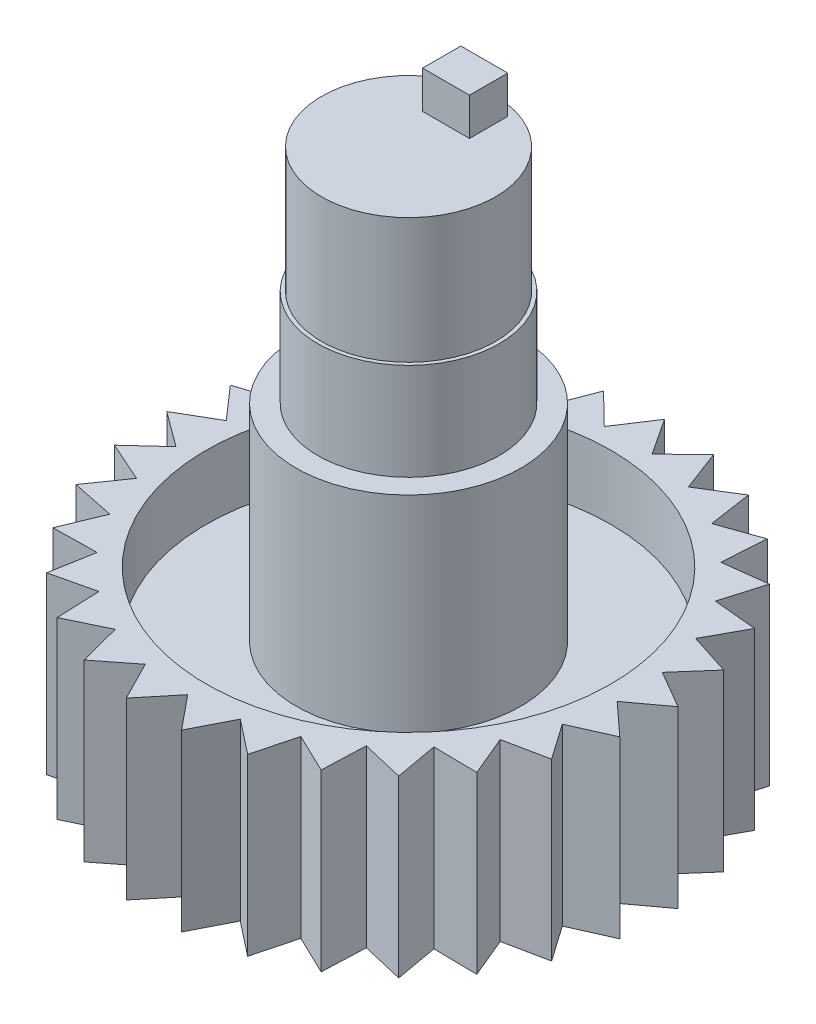
SolidWorks part; units mm, degrees
ref_plane "Front Plane" through (0, 0, 0) normal (0, 0, 1) x (1, 0, 0)
ref_plane "Top Plane" through (0, 0, 0) normal (0, 1, 0) x (1, 0, 0)
ref_plane "Right Plane" through (0, 0, 0) normal (1, 0, 0) x (0, 0, -1)
sketch "Sketch1" plane through (0, 0, 0) normal (0, 0, 1) x (1, 0, 0)
  line L8 (0, 0) -> (0, 24.17)
  line L9 (0, -55) -> (0, 55) construction
  line L10 (0, 24.17) -> (3.25, 24.17)
  line L11 (3.25, 24.17) -> (3.25, 19.49)
  line L12 (3.25, 19.49) -> (3.39, 19.49)
  line L13 (3.39, 19.49) -> (3.39, 15.87)
  line L14 (3.39, 15.87) -> (4.2, 15.87)
  line L15 (4.2, 15.87) -> (4.2, 8.17)
  line L16 (4.2, 8.17) -> (7.56, 8.17)
  line L17 (7.56, 8.17) -> (7.56, 10.57)
  line L18 (7.56, 10.57) -> (9.56, 10.57)
  line L19 (9.56, 10.57) -> (9.56, 4.04)
  line L20 (9.56, 4.04) -> (7.56, 4.04)
  line L21 (7.56, 4.04) -> (7.56, 6.89)
  line L22 (7.56, 6.89) -> (3.365, 6.89)
  line L23 (3.365, 6.89) -> (3.365, 2.46)
  line L24 (3.365, 2.46) -> (2, 2.46)
  line L25 (2, 2.46) -> (2, 0)
  line L26 (55, 0) -> (-55, 0) construction
  line L27 (2, 0) -> (0, 0)
  dimension "D1" = 6.53
  dimension "D2" = 4.2
  dimension "D3" = 9.56
  dimension "D4" = 3.39
  dimension "D5" = 3.25
  dimension "D6" = 4.68
  dimension "D7" = 8.3
  dimension "D8" = 16
  dimension "D9" = 13.6
  dimension "D10" = 2.85
  dimension "D11" = 3.365
  dimension "D12" = 2
  dimension "D13" = 2.46
  dimension "D14" = 4.43
  dimension "D15" = 2
  dimension "D16" = 2
revolve "Revolve1" add sketch "Sketch1" angle 360 about L8
sketch "Sketch2" plane through (0, 24.17, 0) normal (0, 1, 0) x (1, 0, 0)
  line L0 (0, -10.516) -> (0, 10.516) construction
  line L1 (-0.875, 2.83) -> (0.875, 2.83)
  line L2 (-0.875, 2.83) -> (-0.875, 1.4)
  line L3 (-0.875, 1.4) -> (0.875, 1.4)
  line L4 (0.875, 2.83) -> (0.875, 1.4)
  line L5 (-10.516, 0) -> (10.516, 0) construction
  point P4 (0, 2.83)
  dimension "D1" = 1.75
  dimension "D2" = 1.43
  dimension "D3" = 1.4
extrude "Boss-Extrude1" add sketch "Sketch2" along normal blind 1.4
sketch "Sketch3" plane through (0, 10.57, 0) normal (0, 1, 0) x (1, 0, 0)
  line L0 (0, 9.56) -> (-0.892, 8.2016)
  line L1 (0, -10.516) -> (0, 10.516) construction
  line L2 (-0.892, 8.2016) -> (0, 0) construction
  line L3 (0, 0) -> (0.892, 8.2016) construction
  line L4 (0.892, 8.2016) -> (0, 9.56)
  line L5 (2.6342, 7.8181) -> (2.0551, 9.3365)
  line L6 (2.0551, 9.3365) -> (0.892, 8.2016)
  line L7 (4.2533, 7.0691) -> (4.0141, 8.6764)
  line L8 (4.0141, 8.6764) -> (2.6342, 7.8181)
  line L9 (5.6735, 5.9895) -> (5.7855, 7.6106)
  line L10 (5.7855, 7.6106) -> (4.2533, 7.0691)
  line L11 (6.8284, 4.6298) -> (7.2863, 6.189)
  line L12 (7.2863, 6.189) -> (5.6735, 5.9895)
  line L13 (7.6641, 3.0536) -> (8.4464, 4.478)
  line L14 (8.4464, 4.478) -> (6.8284, 4.6298)
  line L15 (8.1413, 1.3347) -> (9.2115, 2.5576)
  line L16 (9.2115, 2.5576) -> (7.6641, 3.0536)
  line L17 (8.2379, -0.4466) -> (9.546, 0.5176)
  line L18 (9.546, 0.5176) -> (8.1413, 1.3347)
  line L19 (7.9493, -2.2071) -> (9.4341, -1.5466)
  line L20 (9.4341, -1.5466) -> (8.2379, -0.4466)
  line L21 (7.289, -3.8644) -> (8.881, -3.5385)
  line L22 (8.881, -3.5385) -> (7.9493, -2.2071)
  line L23 (6.2878, -5.3409) -> (7.9127, -5.3649)
  line L24 (7.9127, -5.3649) -> (7.289, -3.8644)
  line L25 (4.9927, -6.5678) -> (6.5744, -6.9405)
  line L26 (6.5744, -6.9405) -> (6.2878, -5.3409)
  line L27 (3.4641, -7.4875) -> (4.9287, -8.1916)
  line L28 (4.9287, -8.1916) -> (4.9927, -6.5678)
  line L29 (1.7735, -8.0571) -> (3.0525, -9.0596)
  line L30 (3.0525, -9.0596) -> (3.4641, -7.4875)
  line L31 (0, -8.25) -> (1.0336, -9.504)
  line L32 (1.0336, -9.504) -> (1.7735, -8.0571)
  line L33 (-1.7735, -8.0571) -> (-1.0336, -9.504)
  line L34 (-1.0336, -9.504) -> (0, -8.25)
  line L35 (-3.4641, -7.4875) -> (-3.0525, -9.0596)
  line L36 (-3.0525, -9.0596) -> (-1.7735, -8.0571)
  line L37 (-4.9927, -6.5678) -> (-4.9287, -8.1916)
  line L38 (-4.9287, -8.1916) -> (-3.4641, -7.4875)
  line L39 (-6.2878, -5.3409) -> (-6.5744, -6.9405)
  line L40 (-6.5744, -6.9405) -> (-4.9927, -6.5678)
  line L41 (-7.289, -3.8644) -> (-7.9127, -5.3649)
  line L42 (-7.9127, -5.3649) -> (-6.2878, -5.3409)
  line L43 (-7.9493, -2.2071) -> (-8.881, -3.5385)
  line L44 (-8.881, -3.5385) -> (-7.289, -3.8644)
  line L45 (-8.2379, -0.4466) -> (-9.4341, -1.5466)
  line L46 (-9.4341, -1.5466) -> (-7.9493, -2.2071)
  line L47 (-8.1413, 1.3347) -> (-9.546, 0.5176)
  line L48 (-9.546, 0.5176) -> (-8.2379, -0.4466)
  line L49 (-7.6641, 3.0536) -> (-9.2115, 2.5576)
  line L50 (-9.2115, 2.5576) -> (-8.1413, 1.3347)
  line L51 (-6.8284, 4.6298) -> (-8.4464, 4.478)
  line L52 (-8.4464, 4.478) -> (-7.6641, 3.0536)
  line L53 (-5.6735, 5.9895) -> (-7.2863, 6.189)
  line L54 (-7.2863, 6.189) -> (-6.8284, 4.6298)
  line L55 (-4.2533, 7.0691) -> (-5.7855, 7.6106)
  line L56 (-5.7855, 7.6106) -> (-5.6735, 5.9895)
  line L57 (-2.6342, 7.8181) -> (-4.0141, 8.6764)
  line L58 (-4.0141, 8.6764) -> (-4.2533, 7.0691)
  line L59 (-0.892, 8.2016) -> (-2.0551, 9.3365)
  line L60 (-2.0551, 9.3365) -> (-2.6342, 7.8181)
  circle A0 centre (0, 0) radius 8.25 construction
  circle A1 centre (0, 0) radius 9.56 construction
  circle A4 centre (0, 0) radius 10.06
  circle A5 centre (0, 0) radius 10.06
  point P101 (0, 0)
  dimension "D3" = 16.5
  dimension "D2" = 12.414
  dimension "D1" = 0.5
  dimension "D4" = 29
extrude "Cut-Extrude1" cut sketch "Sketch3" against normal through all
